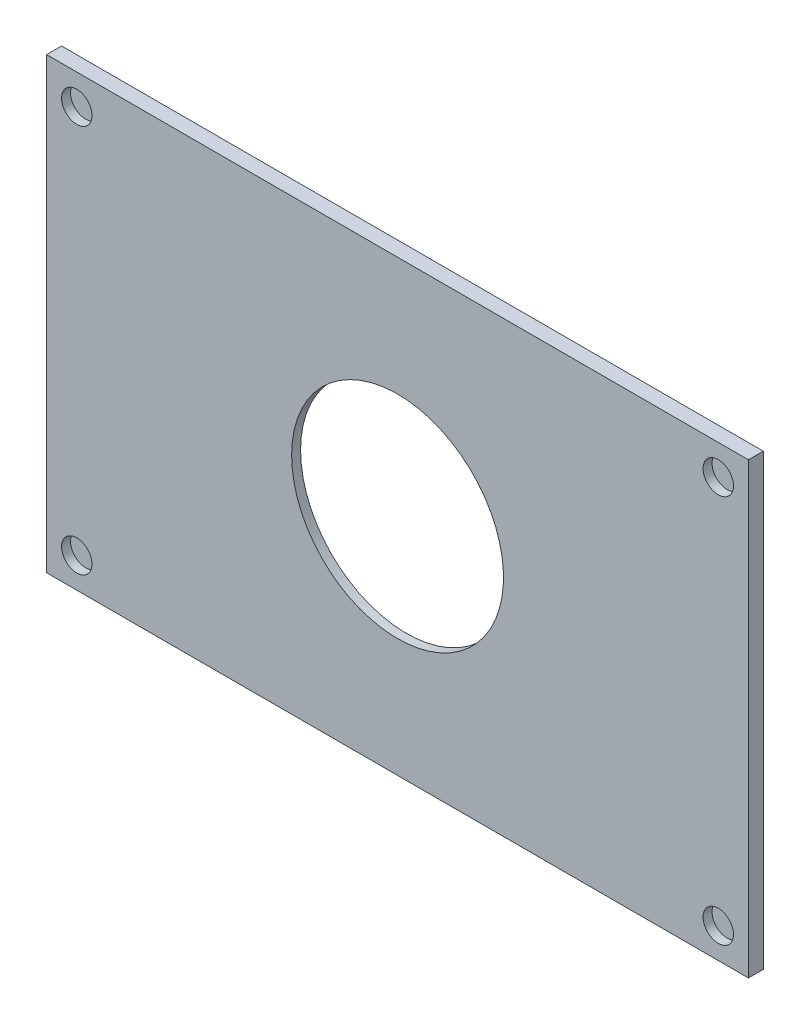
SolidWorks part; units mm, degrees
ref_plane "Front Plane" through (0, 0, 0) normal (0, 0, 1) x (1, 0, 0)
ref_plane "Top Plane" through (0, 0, 0) normal (0, 1, 0) x (1, 0, 0)
ref_plane "Right Plane" through (0, 0, 0) normal (1, 0, 0) x (0, 0, -1)
sketch "Sketch1" plane through (0, 0, 0) normal (0, 0, 1) x (1, 0, 0)
  line L1 (0, 0) -> (298.704, 0)
  line L2 (0, 0) -> (0, -191.008)
  line L3 (0, -191.008) -> (298.704, -191.008)
  line L4 (298.704, 0) -> (298.704, -191.008)
  circle A0 centre (12.827, -12.827) radius 6.477
  circle A1 centre (285.877, -12.827) radius 6.477
  circle A2 centre (285.877, -178.181) radius 6.477
  circle A3 centre (12.827, -178.181) radius 6.477
  circle A4 centre (149.352, -95.504) radius 45.085
  point P0 (-0.1526, 0.1593)
  dimension "D1" = 12.954
  dimension "D4" = 12.954
  dimension "D5" = 273.05
  dimension "D6" = 273.05
  dimension "D2" = 12.954
  dimension "D3" = 12.954
  dimension "D15" = 90.17
  dimension "D7" = 165.354
  dimension "D8" = 165.354
  dimension "D9" = 12.827
  dimension "D10" = 12.827
  dimension "D11" = 12.827
  dimension "D12" = 12.827
  dimension "D13" = 12.827
  dimension "D14" = 12.827
  dimension "D16" = 95.504
  dimension "D17" = 149.352
extrude "Boss-Extrude1" add sketch "Sketch1" along normal blind 3.81
sketch "Sketch3" plane through (0, 0, 0) normal (0, 0, -1) x (-1, 0, 0)
  line L1 (-298.704, -191.008) -> (0, -191.008)
  line L2 (-298.704, -191.008) -> (-298.704, 0)
  line L3 (-298.704, 0) -> (0, 0)
  line L4 (0, -191.008) -> (0, 0)
  circle A0 centre (-149.352, -95.504) radius 47.625
extrude "Boss-Extrude2" add sketch "Sketch3" along normal blind 2.54
sketch "Sketch4" plane through (0, 0, 3.81) normal (0, 0, 1) x (1, 0, 0)
  circle A0 centre (149.352, -95.504) radius 50.165
  dimension "D1" = 100.33
extrude "Cut-Extrude1" cut sketch "Sketch4" against normal blind 2.54 from offset 3.81
